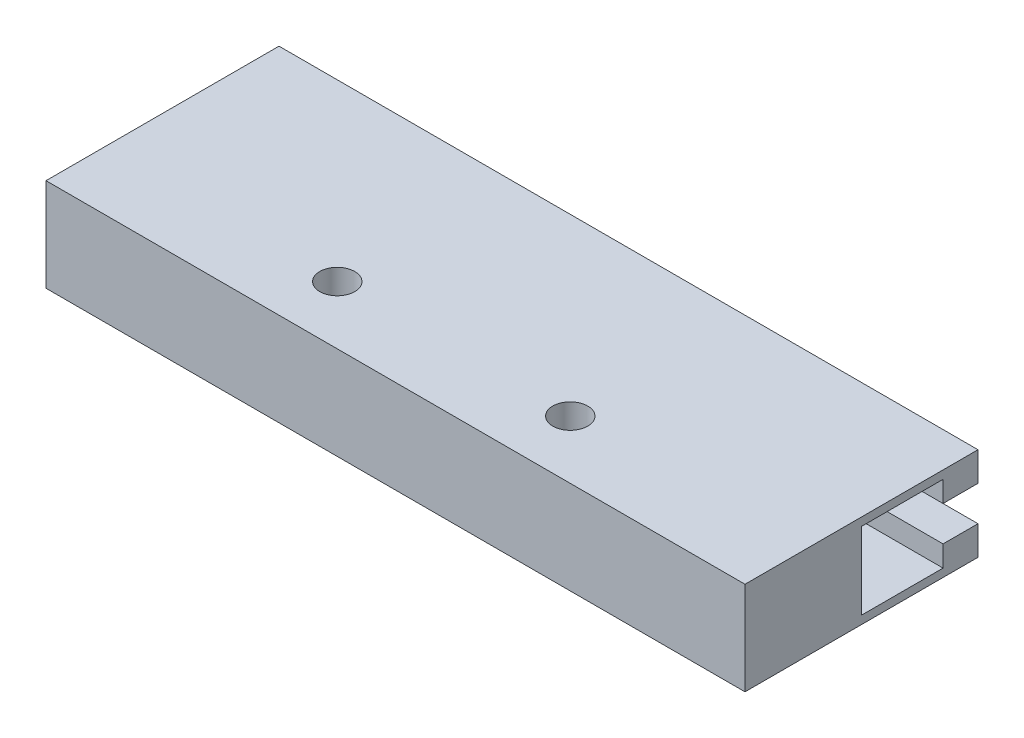
SolidWorks part; units mm, degrees
ref_plane "Front Plane" through (0, 0, 0) normal (0, 0, 1) x (1, 0, 0)
ref_plane "Top Plane" through (0, 0, 0) normal (0, 1, 0) x (1, 0, 0)
ref_plane "Right Plane" through (0, 0, 0) normal (1, 0, 0) x (0, 0, -1)
sketch "Sketch1" plane through (0, 0, 0) normal (0, 0, 1) x (1, 0, 0)
  line L0 (0, 0) -> (60, 0)
  line L1 (60, 0) -> (60, -8)
  line L2 (60, -8) -> (0, -8)
  line L3 (0, -8) -> (0, 0)
  dimension "D1" = 60
  dimension "D2" = 8
extrude "Boss-Extrude1" add sketch "Sketch1" along normal blind 20
sketch "Sketch2" plane through (60, 0, 0) normal (1, 0, 0) x (0, 0, -1)
  line L0 (0, -4) -> (0, -2.5)
  line L1 (0, -8) -> (0, 0) construction
  line L2 (0, -2.5) -> (-3, -2.5)
  line L3 (-3, -2.5) -> (-3, -0.7)
  line L4 (-3, -0.7) -> (-10, -0.7)
  line L5 (-10, -0.7) -> (-10, -7.3)
  line L6 (-10, -7.3) -> (-3, -7.3)
  line L9 (-3, -7.3) -> (-3, -5.5)
  line L10 (-3, -5.5) -> (0, -5.5)
  line L11 (0, -5.5) -> (0, -4)
  dimension "D1" = 1.5
  dimension "D2" = 1.8
  dimension "D3" = 7
  dimension "D4" = 6.6
  dimension "D5" = 7
  dimension "D6" = 1.8
  dimension "D7" = 3
  dimension "D8" = 1.5
extrude "Cut-Extrude1" cut sketch "Sketch2" against normal through all
sketch "Sketch4" plane through (0, 0, 0) normal (0, 1, 0) x (1, 0, 0)
  line L0 (60, -15) -> (0, -15) construction
  line L1 (60, -20) -> (60, 0) construction
  line L2 (0, -20) -> (0, 0) construction
  line L3 (60, -20) -> (0, -20) construction
  circle A0 centre (40, -15) radius 1.5
  circle A1 centre (20, -15) radius 1.5
  dimension "D2" = 20
  dimension "D3" = 20
  dimension "D1" = 5
extrude "Cut-Extrude2" cut sketch "Sketch4" against normal through all
